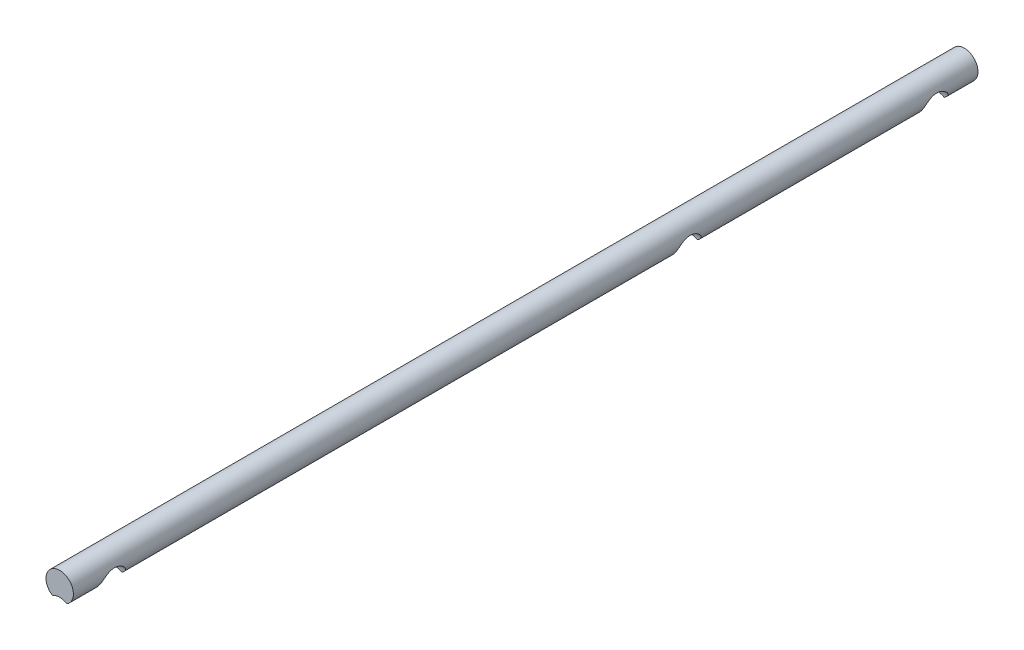
SolidWorks part; units mm, degrees
ref_plane "Спереди" through (0, 0, 0) normal (0, 0, 1) x (1, 0, 0)
ref_plane "Сверху" through (0, 0, 0) normal (0, 1, 0) x (1, 0, 0)
ref_plane "Справа" through (0, 0, 0) normal (1, 0, 0) x (0, 0, -1)
sketch "Эскиз1" plane through (0, 0, 0) normal (0, 0, 1) x (1, 0, 0)
  line L0 (0, 100) -> (0, -70) construction
  circle A0 centre (0, 0) radius 100
  circle A2 centre (0, -175) radius 105
  point P6 (0, 0)
  point P7 (0, 0)
  dimension "D1" = 200
  dimension "D3" = 210
  dimension "D2" = 170
extrude "Бобышка-Вытянуть1" add sketch "Эскиз1" along normal mid plane 6600 contours A0 L0 A2 | L0 A0 A2
sketch "Эскиз2" plane through (0, 0, 0) normal (1, 0, 0) x (0, 0, -1)
  line L0 (-3300, 100) -> (-3300, -84.5714) construction
  line L1 (-3300, -84.5714) -> (3300, -84.5714) construction
  line L2 (0, 0) -> (0, 114.413) construction
  circle A0 centre (-3000, -84.5714) radius 100
  circle A1 centre (3000, -84.5714) radius 100
  circle A2 centre (1200, -84.5714) radius 100
  dimension "D2" = 200
  dimension "D1" = 300
  dimension "D3" = 1800
extrude "Вырез-Вытянуть1" cut sketch "Эскиз2" against normal mid plane 6000
sketch "Эскиз3" plane through (0, 0, 0) normal (0, 1, 0) x (1, 0, 0)
  line L0 (-100, -3300) -> (100, -3300) construction
  line L1 (0, -2920.923) -> (0, -3079.077) construction
  line L2 (-79.077, -3000) -> (79.077, -3000) construction
  line L3 (0, 0) -> (163.9977, 0) construction
  line L4 (-79.077, 3000) -> (79.077, 3000) construction
  line L5 (0, 2920.923) -> (0, 3079.077) construction
  line L6 (79.077, 1200) -> (-79.077, 1200) construction
  line L7 (0, 1120.923) -> (0, 1279.077) construction
  circle A0 centre (0, -3000) radius 79.077 construction
  circle A1 centre (0, 3000) radius 79.077 construction
  circle A2 centre (0, 1200) radius 79.077 construction
  dimension "D2" = 158.1541
  dimension "D1" = 300
  dimension "D3" = 1800
equation "\"Длина\"= 6000 + 600"
equation "\"D1@Бобышка-Вытянуть1\"=\"Длина\""
